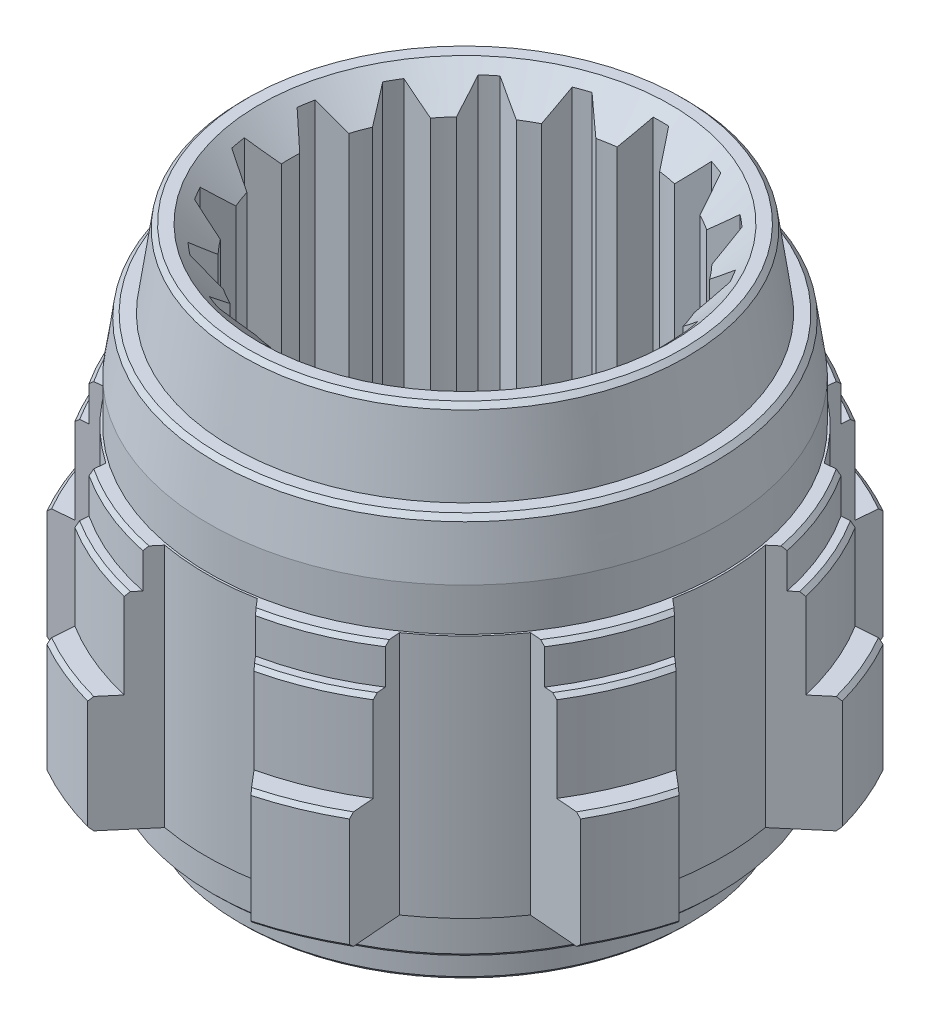
SolidWorks part; units mm, degrees
ref_plane "Plano frontal" through (0, 0, 0) normal (0, 0, 1) x (1, 0, 0)
ref_plane "Plano superior" through (0, 0, 0) normal (0, 1, 0) x (1, 0, 0)
ref_plane "Plano direito" through (0, 0, 0) normal (1, 0, 0) x (0, 0, -1)
sketch "Esboço1" plane through (0, 0, 0) normal (0, 0, 1) x (1, 0, 0)
  line L0 (11.0794, -43.6672) -> (11.0794, 39.9332) construction
  line L1 (33.5794, 39.9332) -> (39.5794, 39.9332)
  line L2 (39.5794, 39.9332) -> (41.008, 29.9332)
  line L3 (41.008, 29.9332) -> (43.0794, 29.9332)
  line L4 (43.0794, 29.9332) -> (44.0794, 22.9332)
  line L5 (44.0794, 22.9332) -> (44.0794, 17.4332)
  line L6 (44.0794, 17.4332) -> (46.0794, 17.4332)
  line L7 (46.0794, 12.4332) -> (47.5794, 12.4332)
  line L8 (47.5794, 12.4332) -> (47.5794, 0.9332)
  line L9 (47.5794, 0.9332) -> (50.5794, 0.9332)
  line L10 (50.5794, 0.9332) -> (50.5794, -14.0668)
  line L11 (50.5794, -14.0668) -> (43.5794, -14.0668)
  line L12 (43.5794, -14.0668) -> (43.5794, -19.0668)
  line L13 (43.5794, -19.0668) -> (40.0794, -19.0668)
  line L14 (40.0794, -19.0668) -> (40.0794, -24.0668)
  line L15 (46.0794, 17.4332) -> (46.0794, 12.4332)
  line L17 (40.0794, -24.0668) -> (33.5794, -24.0668)
  line L18 (33.5794, -24.0668) -> (33.5794, 39.9332)
  dimension "D1" = 64
  dimension "D2" = 22.5
  dimension "D3" = 28.5
  dimension "D4" = 32
  dimension "D5" = 10
  dimension "D6" = 7
  dimension "D7" = 12.5
  dimension "D8" = 5
  dimension "D9" = 11.5
  dimension "D10" = 15
  dimension "D11" = 5
  dimension "D12" = 5
  dimension "D13" = 33
  dimension "D14" = 35
  dimension "D15" = 36.5
  dimension "D16" = 39.5
  dimension "D17" = 32.5
  dimension "D18" = 29
revolve "Revolução1" add sketch "Esboço1" angle 360 about L0
chamfer "Chanfro1" distance 4 angle 45 1 edges at (11.0794, 39.9332, -22.5)
chamfer "Chanfro2" distance 4 angle 45 1 edges at (11.0794, -24.0668, -22.5)
sketch "Esboço2" plane through (0, -14.0668, 0) normal (0, -1, 0) x (1, 0, 0)
  line L0 (-28.4206, 0) -> (50.5794, 0) construction
  line L1 (11.0794, -39.5) -> (11.0794, 39.5) construction
  line L2 (30.5632, 34.3603) -> (29.9933, 27.3464)
  line L3 (38.4258, 18.9139) -> (45.4397, 19.4838)
  line L4 (49.153, 10.5193) -> (43.7904, 5.9627)
  line L5 (43.7904, -5.9627) -> (49.153, -10.5193)
  line L6 (45.4397, -19.4838) -> (38.4258, -18.9139)
  line L7 (29.9933, -27.3464) -> (30.5632, -34.3603)
  line L8 (0.5601, 38.0735) -> (5.1167, 32.711)
  line L9 (17.0421, 32.711) -> (21.5987, 38.0735)
  line L10 (21.5987, -38.0735) -> (17.0421, -32.711)
  line L11 (5.1167, -32.711) -> (0.5601, -38.0735)
  line L12 (-8.4044, -34.3603) -> (-7.8345, -27.3464)
  line L13 (-16.267, -18.9139) -> (-23.2809, -19.4838)
  line L14 (-26.9941, -10.5193) -> (-21.6316, -5.9627)
  line L15 (-21.6316, 5.9627) -> (-26.9941, 10.5193)
  line L16 (-23.2809, 19.4838) -> (-16.267, 18.9139)
  line L17 (-7.8345, 27.3464) -> (-8.4044, 34.3603)
  circle A0 centre (11.0794, 0) radius 39.5 construction
  circle A1 centre (11.0794, 0) radius 33.25
  arc A2 (0.5601, 38.0735) -> (21.5987, 38.0735) centre (11.0794, 0) cw
  arc A3 (5.1167, 32.711) -> (17.0421, 32.711) centre (11.0794, 0) cw
  arc A4 (30.5632, 34.3603) -> (45.4397, 19.4838) centre (11.0794, 0) cw
  arc A5 (29.9933, 27.3464) -> (38.4258, 18.9139) centre (11.0794, 0) cw
  arc A6 (49.153, 10.5193) -> (49.153, -10.5193) centre (11.0794, 0) cw
  arc A7 (43.7904, 5.9627) -> (43.7904, -5.9627) centre (11.0794, 0) cw
  arc A8 (45.4397, -19.4838) -> (30.5632, -34.3603) centre (11.0794, 0) cw
  arc A9 (38.4258, -18.9139) -> (29.9933, -27.3464) centre (11.0794, 0) cw
  arc A10 (21.5987, -38.0735) -> (0.5601, -38.0735) centre (11.0794, 0) cw
  arc A11 (17.0421, -32.711) -> (5.1167, -32.711) centre (11.0794, 0) cw
  arc A12 (-8.4044, -34.3603) -> (-23.2809, -19.4838) centre (11.0794, 0) cw
  arc A13 (-7.8345, -27.3464) -> (-16.267, -18.9139) centre (11.0794, 0) cw
  arc A14 (-26.9941, -10.5193) -> (-26.9941, 10.5193) centre (11.0794, 0) cw
  arc A15 (-21.6316, -5.9627) -> (-21.6316, 5.9627) centre (11.0794, 0) cw
  arc A16 (-23.2809, 19.4838) -> (-8.4044, 34.3603) centre (11.0794, 0) cw
  arc A17 (-16.267, 18.9139) -> (-7.8345, 27.3464) centre (11.0794, 0) cw
  circle M3 centre (11.0794, 0) radius 39.5
  dimension "D1" = 66.5
  dimension "D2" = 8
extrude "Corte-extrusão1" cut sketch "Esboço2" against normal through all contours A1 L9 L8 M3 | A1 L17 L16 M3 | A1 L15 L14 M3 | A1 L13 L12 M3 | A1 L11 L10 M3 | A1 L7 L6 M3 | A1 L5 L4 M3 | A4 L3 A5 L2
sketch "Esboço3" plane through (0, -24.0668, 0) normal (0, -1, 0) x (1, 0, 0)
  line L0 (11.0794, 26.5) -> (11.0794, -26.5) construction
  line L1 (-15.4206, 0) -> (37.5794, 0) construction
  line L2 (10.0811, 25.2303) -> (8.3456, 22.3333)
  line L3 (12.0778, 25.2303) -> (13.8132, 22.3333)
  line L4 (18.7705, 24.0501) -> (16.1489, 21.9215)
  line L5 (20.6468, 23.3672) -> (21.2868, 20.0514)
  line L6 (26.5323, 19.9692) -> (23.3408, 18.8656)
  line L7 (28.0619, 18.6858) -> (27.5292, 15.351)
  line L8 (32.4303, 13.4797) -> (29.0537, 13.5342)
  line L9 (33.4286, 11.7505) -> (31.7875, 8.7991)
  line L10 (35.753, 5.3644) -> (32.5987, 6.5704)
  line L11 (36.0997, 3.398) -> (33.5481, 1.1859)
  line L12 (36.0997, -3.398) -> (33.5481, -1.1859)
  line L13 (35.753, -5.3644) -> (32.5987, -6.5704)
  line L14 (33.4286, -11.7505) -> (31.7875, -8.7991)
  line L15 (32.4303, -13.4797) -> (29.0537, -13.5342)
  line L16 (28.0619, -18.6858) -> (27.5292, -15.351)
  line L17 (26.5323, -19.9692) -> (23.3408, -18.8656)
  line L18 (20.6468, -23.3672) -> (21.2868, -20.0514)
  line L19 (18.7705, -24.0501) -> (16.1489, -21.9215)
  line L20 (12.0778, -25.2303) -> (13.8132, -22.3333)
  line L21 (10.0811, -25.2303) -> (8.3456, -22.3333)
  line L22 (3.3883, -24.0501) -> (6.0099, -21.9215)
  line L23 (1.512, -23.3672) -> (0.872, -20.0514)
  line L24 (-4.3735, -19.9692) -> (-1.1819, -18.8656)
  line L25 (-5.9031, -18.6858) -> (-5.3704, -15.351)
  line L26 (-10.2714, -13.4797) -> (-6.8949, -13.5342)
  line L27 (-11.2698, -11.7505) -> (-9.6287, -8.7991)
  line L28 (-13.5942, -5.3644) -> (-10.4399, -6.5704)
  line L29 (-13.9409, -3.398) -> (-11.3893, -1.1859)
  line L30 (-13.9409, 3.398) -> (-11.3893, 1.1859)
  line L31 (-13.5942, 5.3644) -> (-10.4399, 6.5704)
  line L32 (-11.2698, 11.7505) -> (-9.6287, 8.7991)
  line L33 (-10.2714, 13.4797) -> (-6.8949, 13.5342)
  line L34 (-5.9031, 18.6858) -> (-5.3704, 15.351)
  line L35 (-4.3735, 19.9692) -> (-1.1819, 18.8656)
  line L36 (1.512, 23.3672) -> (0.872, 20.0514)
  line L37 (3.3883, 24.0501) -> (6.0099, 21.9215)
  circle A0 centre (11.0794, 0) radius 26.5 construction
  arc A1 (18.7705, 24.0501) -> (20.6468, 23.3672) centre (11.0794, 0) cw
  arc A2 (10.0811, 25.2303) -> (12.0778, 25.2303) centre (11.0794, 0) cw
  circle A3 centre (11.0794, 0) radius 22.5 construction
  arc A4 (8.3456, 22.3333) -> (13.8132, 22.3333) centre (11.0794, 0) cw
  arc A5 (16.1489, 21.9215) -> (21.2868, 20.0514) centre (11.0794, 0) cw
  arc A6 (26.5323, 19.9692) -> (28.0619, 18.6858) centre (11.0794, 0) cw
  arc A7 (23.3408, 18.8656) -> (27.5292, 15.351) centre (11.0794, 0) cw
  arc A8 (32.4303, 13.4797) -> (33.4286, 11.7505) centre (11.0794, 0) cw
  arc A9 (29.0537, 13.5342) -> (31.7875, 8.7991) centre (11.0794, 0) cw
  arc A10 (35.753, 5.3644) -> (36.0997, 3.398) centre (11.0794, 0) cw
  arc A11 (32.5987, 6.5704) -> (33.5481, 1.1859) centre (11.0794, 0) cw
  arc A12 (36.0997, -3.398) -> (35.753, -5.3644) centre (11.0794, 0) cw
  arc A13 (33.5481, -1.1859) -> (32.5987, -6.5704) centre (11.0794, 0) cw
  arc A14 (33.4286, -11.7505) -> (32.4303, -13.4797) centre (11.0794, 0) cw
  arc A15 (31.7875, -8.7991) -> (29.0537, -13.5342) centre (11.0794, 0) cw
  arc A16 (28.0619, -18.6858) -> (26.5323, -19.9692) centre (11.0794, 0) cw
  arc A17 (27.5292, -15.351) -> (23.3408, -18.8656) centre (11.0794, 0) cw
  arc A18 (20.6468, -23.3672) -> (18.7705, -24.0501) centre (11.0794, 0) cw
  arc A19 (21.2868, -20.0514) -> (16.1489, -21.9215) centre (11.0794, 0) cw
  arc A20 (12.0778, -25.2303) -> (10.0811, -25.2303) centre (11.0794, 0) cw
  arc A21 (13.8132, -22.3333) -> (8.3456, -22.3333) centre (11.0794, 0) cw
  arc A22 (3.3883, -24.0501) -> (1.512, -23.3672) centre (11.0794, 0) cw
  arc A23 (6.0099, -21.9215) -> (0.872, -20.0514) centre (11.0794, 0) cw
  arc A24 (-4.3735, -19.9692) -> (-5.9031, -18.6858) centre (11.0794, 0) cw
  arc A25 (-1.1819, -18.8656) -> (-5.3704, -15.351) centre (11.0794, 0) cw
  arc A26 (-10.2714, -13.4797) -> (-11.2698, -11.7505) centre (11.0794, 0) cw
  arc A27 (-6.8949, -13.5342) -> (-9.6287, -8.7991) centre (11.0794, 0) cw
  arc A28 (-13.5942, -5.3644) -> (-13.9409, -3.398) centre (11.0794, 0) cw
  arc A29 (-10.4399, -6.5704) -> (-11.3893, -1.1859) centre (11.0794, 0) cw
  arc A30 (-13.9409, 3.398) -> (-13.5942, 5.3644) centre (11.0794, 0) cw
  arc A31 (-11.3893, 1.1859) -> (-10.4399, 6.5704) centre (11.0794, 0) cw
  arc A32 (-11.2698, 11.7505) -> (-10.2714, 13.4797) centre (11.0794, 0) cw
  arc A33 (-9.6287, 8.7991) -> (-6.8949, 13.5342) centre (11.0794, 0) cw
  arc A34 (-5.9031, 18.6858) -> (-4.3735, 19.9692) centre (11.0794, 0) cw
  arc A35 (-5.3704, 15.351) -> (-1.1819, 18.8656) centre (11.0794, 0) cw
  arc A36 (1.512, 23.3672) -> (3.3883, 24.0501) centre (11.0794, 0) cw
  arc A37 (0.872, 20.0514) -> (6.0099, 21.9215) centre (11.0794, 0) cw
  dimension "D1" = 18
extrude "Corte-extrusão2" cut sketch "Esboço3" against normal through all
chamfer "Chanfro3" distance 0.5 angle 45 21 edges at (-25.4138, -14.0668, -15.116) (-25.4138, 0.9332, -15.116) (-22.6422, 12.4332, -13.9679) (-21.2564, 17.4332, -13.3939) (-2.3145, 17.4332, -32.3358) (-2.8885, 12.4332, -33.7216) (-4.0366, 0.9332, -36.4932) (-4.0366, -14.0668, -36.4932) (26.1954, -14.0668, -36.4932) (26.1954, 0.9332, -36.4932) (25.0474, 12.4332, -33.7216) (24.4733, 17.4332, -32.3358) (47.5727, -14.0668, -15.116) (47.5727, 0.9332, -15.116) (47.5727, 0.9332, 15.116) (44.801, 12.4332, 13.9679) (43.4152, 17.4332, 13.3939) (44.801, 12.4332, -13.9679) (43.4152, 17.4332, -13.3939) (11.0794, 29.9332, -32) (11.0794, 39.9332, -28.5)
chamfer "Chanfro4" distance 0.5 angle 45 13 edges at (47.5727, -14.0668, 15.116) (26.1954, -14.0668, 36.4932) (26.1954, 0.9332, 36.4932) (25.0474, 12.4332, 33.7216) (24.4733, 17.4332, 32.3358) (-4.0366, -14.0668, 36.4932) (-4.0366, 0.9332, 36.4932) (-2.8885, 12.4332, 33.7216) (-2.3145, 17.4332, 32.3358) (-25.4138, -14.0668, 15.116) (-25.4138, 0.9332, 15.116) (-22.6422, 12.4332, 13.9679) (-21.2564, 17.4332, 13.3939)
chamfer "Chanfro5" distance 0.5 angle 45 2 edges at (11.0794, -24.0668, -29) (11.0794, -19.0668, -32.5)
fillet "Filete1" radius 0.5 2 edges at (11.0794, -14.0668, -32.5) (11.0794, -19.0668, -29)
